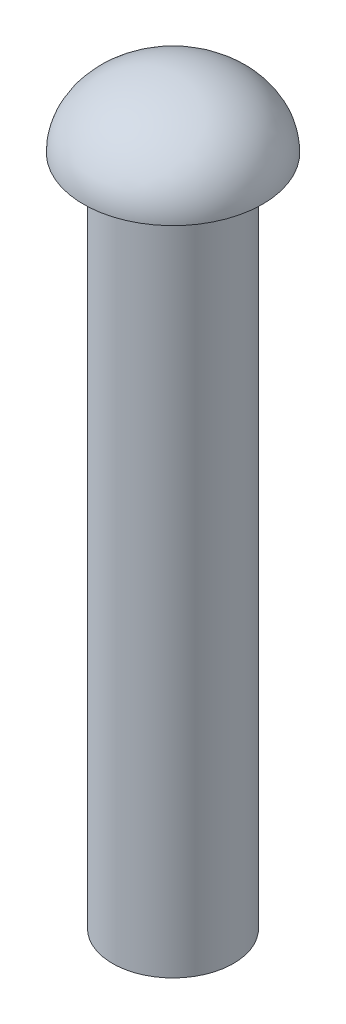
SolidWorks part; units mm, degrees
ref_plane "Front Plane" through (0, 0, 0) normal (0, 0, 1) x (1, 0, 0)
ref_plane "Top Plane" through (0, 0, 0) normal (0, 1, 0) x (1, 0, 0)
ref_plane "Right Plane" through (0, 0, 0) normal (1, 0, 0) x (0, 0, -1)
sketch "Sketch1" plane through (0, 0, 0) normal (0, 1, 0) x (1, 0, 0)
  circle A0 centre (0, 0) radius 1.3716
extrude "Boss-Extrude1" add sketch "Sketch1" along normal blind 15.24
sketch3d "3DSketch1" plane through (0, 0, 0) normal (0, 0, 1) x (1, 0, 0)
sketch "Sketch2" plane through (0, 0, 0) normal (0, 0, -1) x (-1, 0, 0)
  line L0 (0, 0) -> (0, 15.24)
  line L1 (0, 15.24) -> (-2.032, 15.24)
  line L2 (0, 15.24) -> (0, 16.764)
  ellipse E0 centre (0, 15.24) end of major axis (-2.032, 15.24) minor radius 1.524 (-2.032, 15.24) -> (0, 16.764) cw
revolve "Revolve1" add sketch "Sketch2" angle 360 about L2
